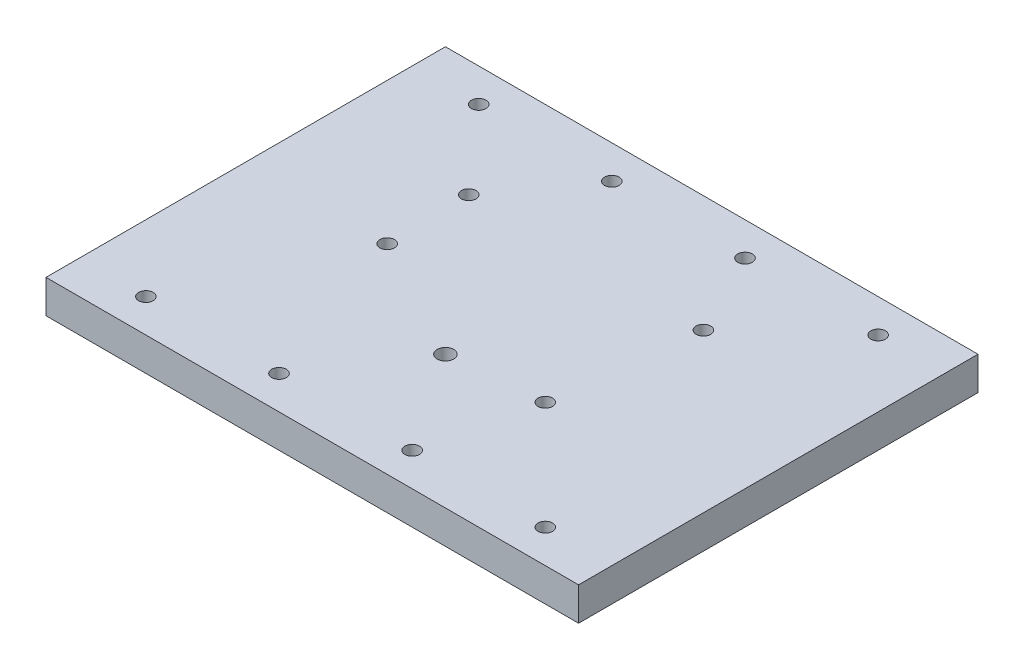
SolidWorks part; units mm, degrees
material "Pine"
ref_plane "Front Plane" through (0, 0, 0) normal (0, 0, 1) x (1, 0, 0)
ref_plane "Top Plane" through (0, 0, 0) normal (0, 1, 0) x (1, 0, 0)
ref_plane "Right Plane" through (0, 0, 0) normal (1, 0, 0) x (0, 0, -1)
sketch "Sketch1" plane through (0, 0, 0) normal (0, 1, 0) x (1, 0, 0)
  line L1 (0, 0) -> (203.2, 0)
  line L2 (0, 0) -> (0, 152.4)
  line L3 (0, 152.4) -> (203.2, 152.4)
  line L4 (203.2, 0) -> (203.2, 152.4)
  dimension "D1" = 152.4
  dimension "D2" = 203.2
extrude "Boss-Extrude1" add sketch "Sketch1" along normal blind 12.7
sketch "Sketch2" plane through (0, 12.7, 0) normal (0, 1, 0) x (1, 0, 0)
  line L0 (203.2, 152.4) -> (0, 152.4) construction
  line L1 (0, 152.4) -> (0, 0) construction
  line L2 (0, 0) -> (203.2, 0) construction
  circle A0 centre (25.4, 139.7) radius 2.7781
  circle A1 centre (25.4, 12.7) radius 2.7781
  point P10 (0, 0)
  point P11 (0, 0)
  point P12 (0, 0)
  dimension "D1" = 5.5562
  dimension "D4" = 5.5562
  dimension "D2" = 12.7
  dimension "D3" = 25.4
  dimension "D5" = 12.7
extrude "Cut-Extrude1" cut sketch "Sketch2" against normal through all
pattern_linear "LPattern1" count 4 spacing 50.8 along (1, 0, 0) of "Cut-Extrude1"
sketch "Sketch4" plane through (0, 12.7, 0) normal (0, 1, 0) x (1, 0, 0)
  line L0 (0, 152.4) -> (0, 0) construction
  line L1 (0, 0) -> (203.2, 0) construction
  circle A0 centre (53.975, 76.2) radius 2.7781
  circle A1 centre (53.34, 107.95) radius 2.7781
  circle A2 centre (101.6, 50.8) radius 3.175
  circle A3 centre (142.875, 107.95) radius 2.7781
  circle A4 centre (136.525, 53.975) radius 2.7781
  circle A5 centre (25.4, 139.7) radius 2.7781 construction
  dimension "D1" = 6.35
  dimension "D5" = 107.95
  dimension "D6" = 53.34
  dimension "D7" = 53.975
  dimension "D2" = 101.6
  dimension "D3" = 50.8
  dimension "D4" = 76.2
  dimension "D8" = 136.525
  dimension "D9" = 142.875
  dimension "D10" = 53.975
  dimension "D11" = 107.95
extrude "Cut-Extrude2" cut sketch "Sketch4" against normal through all
